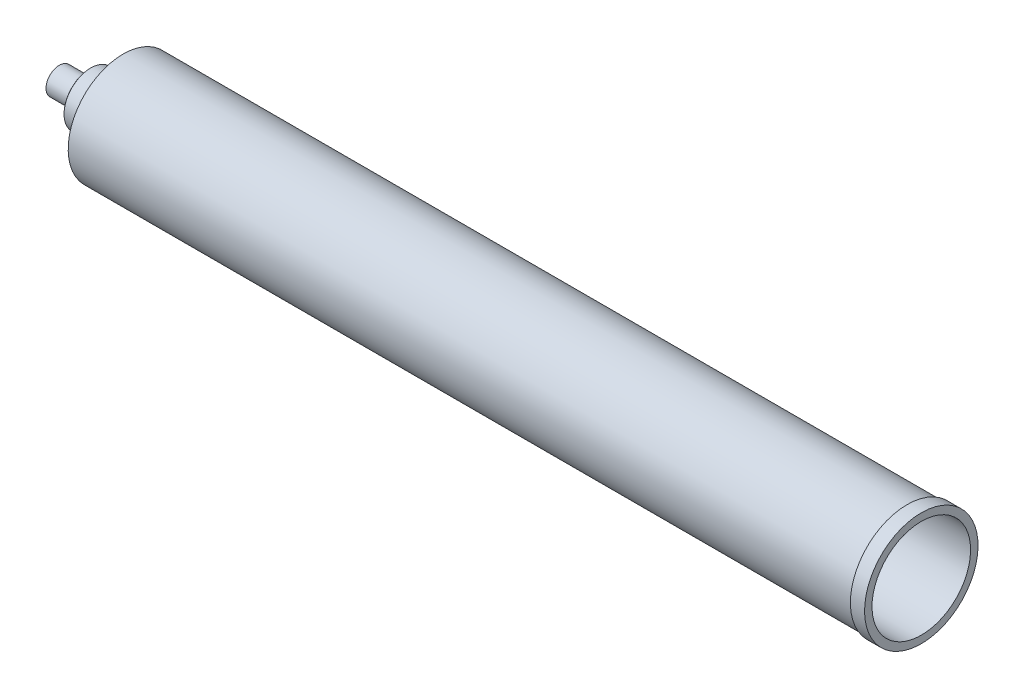
SolidWorks part; units mm, degrees
ref_plane "Front Plane" through (0, 0, 0) normal (0, 0, 1) x (1, 0, 0)
ref_plane "Top Plane" through (0, 0, 0) normal (0, 1, 0) x (1, 0, 0)
ref_plane "Right Plane" through (0, 0, 0) normal (1, 0, 0) x (0, 0, -1)
sketch "Sketch1" plane through (0, 0, 0) normal (0, 0, 1) x (1, 0, 0)
  line L0 (0, 0) -> (0, 11.938)
  line L1 (0, 11.938) -> (24.765, 11.938)
  line L2 (27.305, 14.478) -> (27.305, 22.933)
  line L3 (28.1044, 23.876) -> (57.15, 23.876)
  line L4 (57.15, 23.876) -> (57.15, 49.2125)
  line L5 (57.15, 49.2125) -> (759.206, 49.2125)
  line L6 (771.906, 49.2125) -> (771.906, 44.1325)
  line L7 (62.23, 0) -> (0, 0)
  line L8 (27.305, 22.933) -> (28.1044, 23.876)
  line L11 (62.23, 0) -> (62.23, 44.1325)
  line L12 (62.23, 44.1325) -> (771.906, 44.1325)
  line L14 (759.206, 49.2125) -> (759.206, 50.8)
  line L15 (759.206, 50.8) -> (771.906, 50.8)
  line L16 (771.906, 49.2125) -> (771.906, 50.8)
  arc A0 (24.765, 11.938) -> (27.305, 14.478) centre (24.765, 14.478) ccw
  point P11 (27.305, 11.938)
  dimension "D1" = 11.938
  dimension "D7" = 2.54
  dimension "D2" = 25.3365
  dimension "D3" = 49.2125
  dimension "D4" = 28.1044
  dimension "D5" = 27.305
  dimension "D6" = 702.056
  dimension "D8" = 57.15
  dimension "D9" = 22.933
  dimension "D10" = 5.08
  dimension "D11" = 5.08
  dimension "D12" = 50.8
  dimension "D13" = 12.7
revolve "Revolve1" add sketch "Sketch1" angle 360 about L7
sketch "Sketch16" plane through (0, 0, 0) normal (0, 1, 0) x (1, 0, 0)
  line L0 (0, 0) -> (0, 8.3503)
  line L1 (0, 8.3503) -> (1.905, 8.3503) construction
  line L2 (1.905, 8.3503) -> (1.905, 6.5564) construction
  line L3 (1.905, 6.5564) -> (0, 8.3503)
  line L4 (1.905, 6.5564) -> (1.905, 0)
  line L5 (-54.1337, 0) -> (54.1337, 0) construction
  line L6 (1.905, 0) -> (0, 0)
  dimension "D1" = 8.3503
  dimension "D2" = 6.5564
  dimension "D3" = 1.905
revolve "Cut-Revolve1" cut sketch "Sketch16" angle 360 about L6
sketch "Sketch19" plane through (1.905, 0, 0) normal (-1, 0, 0) x (0, 0, 1)
  circle A0 centre (0, 0) radius 4
  dimension "D1" = 8
extrude "Cut-Extrude3" cut sketch "Sketch19" against normal blind 25.4
sketch "Sketch32" plane through (0, 0, 0) normal (0, 1, 0) x (1, 0, 0)
  line L1 (-55, 0) -> (55, 0) construction
  line L2 (27.305, 0) -> (28.575, 0)
  line L3 (27.305, 0) -> (27.305, 6.3511)
  line L4 (27.305, 22.933) -> (27.305, -22.933) construction
  line L5 (27.305, 6.3511) -> (28.575, 0)
  dimension "D1" = 6.3511
  dimension "D2" = 1.27
  dimension "D3" = 27.305
revolve "Cut-Revolve6" cut sketch "Sketch32" angle 360 about L2
